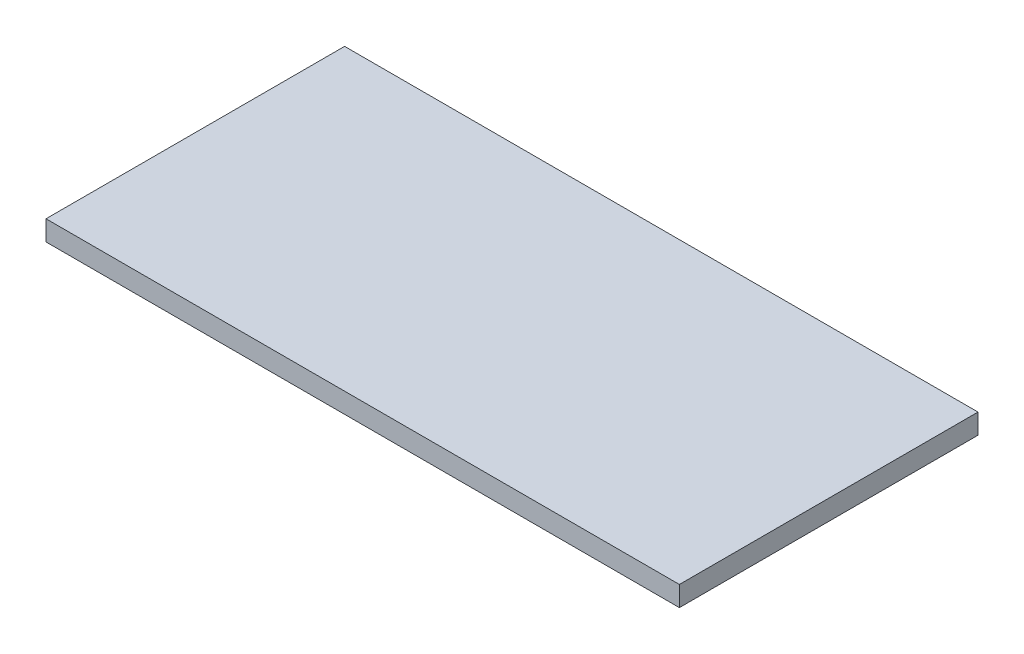
SolidWorks part; units mm, degrees
ref_plane "Front Plane" through (0, 0, 0) normal (0, 0, 1) x (1, 0, 0)
ref_plane "Top Plane" through (0, 0, 0) normal (0, 1, 0) x (1, 0, 0)
ref_plane "Right Plane" through (0, 0, 0) normal (1, 0, 0) x (0, 0, -1)
sketch "Sketch1" plane through (0, 0, 0) normal (0, 1, 0) x (1, 0, 0)
  line L1 (-47.3, -22.3) -> (47.3, -22.3)
  line L2 (-47.3, -22.3) -> (-47.3, 22.3)
  line L3 (-47.3, 22.3) -> (47.3, 22.3)
  line L4 (47.3, -22.3) -> (47.3, 22.3)
  line L5 (-47.3, -22.3) -> (47.3, 22.3) construction
  line L6 (-47.3, 22.3) -> (47.3, -22.3) construction
  point P0 (0, 0)
  dimension "D1" = 94.6
  dimension "D2" = 44.6
extrude "Boss-Extrude1" add sketch "Sketch1" along normal blind 3
